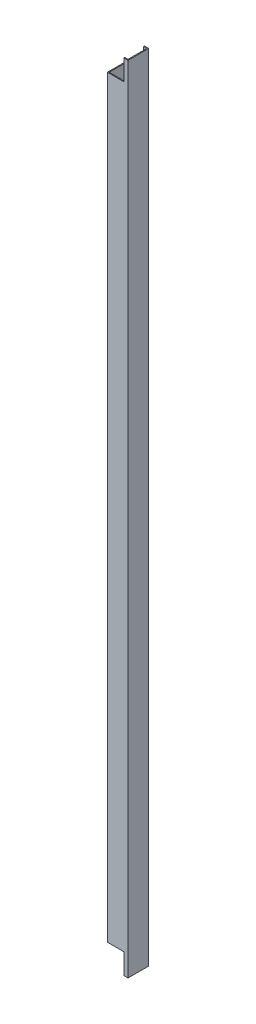
SolidWorks part; units mm, degrees
ref_plane "Front Plane" through (0, 0, 0) normal (0, 0, 1) x (1, 0, 0)
ref_plane "Top Plane" through (0, 0, 0) normal (0, 1, 0) x (1, 0, 0)
ref_plane "Right Plane" through (0, 0, 0) normal (1, 0, 0) x (0, 0, -1)
sketch "Sketch1" plane through (0, 0, 0) normal (0, 1, 0) x (1, 0, 0)
  line L0 (0, 0) -> (0, 50)
  line L1 (0, 50) -> (50, 50)
  line L2 (50, 50) -> (50, 0)
  line L3 (50, 0) -> (0, 0)
  line L4 (2.2, 47.8) -> (47.8, 47.8)
  line L5 (47.8, 47.8) -> (47.8, 2.2)
  line L6 (47.8, 2.2) -> (2.2, 2.2)
  line L7 (2.2, 2.2) -> (2.2, 47.8)
  dimension "D1" = 50
  dimension "D2" = 50
  dimension "D3" = 2.2
extrude "Boss-Extrude1" add sketch "Sketch1" along normal blind 1923
sketch "Sketch2" plane through (0, 0, 0) normal (0, 0, 1) x (1, 0, 0)
  line L0 (0, 0) -> (0, 50)
  line L1 (0, 1923) -> (0, 0) construction
  line L2 (0, 50) -> (40, 50)
  line L3 (40, 50) -> (40, 0)
  line L5 (40, 0) -> (0, 0)
  line L6 (0, 1923) -> (40, 1923)
  line L7 (0, 1923) -> (50, 1923) construction
  line L8 (40, 1923) -> (40, 1873)
  line L9 (40, 1873) -> (0, 1873)
  line L10 (0, 1873) -> (0, 1923)
  dimension "D1" = 50
  dimension "D2" = 40
  dimension "D3" = 50
  dimension "D4" = 40
extrude "Cut-Extrude2" cut sketch "Sketch2" against normal blind 50
equation "\"SquareTube_length\"=1923.0"
equation "\"D1@Boss-Extrude1\"=\"SquareTube_length\""
equation "\"SquareTube_inFront1_cutDepth50_R\"=0.5"
equation "\"D1@Sketch2\" = \"SquareTube_inFront12_cutDepth50_R\""
equation "\"SquareTube_inFront1_cutDepth50_L\"=0.5"
equation "\"D3@Sketch2\" = \"SquareTube_inFront12_cutDepth50_L\""
equation "\"CarBeamWidth\"=700.0"
equation "\"MetalSheet_3mm_length\"=5030.0"
equation "\"MetalSheet_3mm_width\"=1923.0"
equation "\"MetalSheet_3mm_FloorCut_L_length\"=1764.0"
equation "\"MetalSheet_3mm_FloorCut_L_disdance\"=1665.0"
equation "\"MetalSheet_3mm_FloorCut_R_length\"=1764.0"
equation "\"MetalSheet_3mm_FloorCut_R_disdance\"=1665.0"
equation "\"indoorHeight\"=1940.0"
equation "\"x\"=66.0"
equation "\"da\"=62.0"
equation "\"SquareTube_wheel_length\"= 750"
equation "\"channelSteel_length\"=5030.0"
equation "\"SquareTube_inFront2_cutDepth50_R\"=0.5"
equation "\"SquareTube_inFront2_cutDepth50_L\"=0.5"
equation "\"SquareTube_inFront3_cutDepth50_R\"=0.5"
equation "\"SquareTube_inFront3_cutDepth50_L\"=0.5"
equation "\"SquareTube_inFront4_cutDepth50_R\"=0.5"
equation "\"SquareTube_inFront4_cutDepth50_L\"=0.5"
equation "\"SquareTube_inFront5_cutDepth50_R\"=50"
equation "\"SquareTube_inFront5_cutDepth50_L\"=50"
equation "\"SquareTube_inFront6_cutDepth50_R\"=50"
equation "\"SquareTube_inFront6_cutDepth50_L\"=50"
equation "\"SquareTube_inFront7_cutDepth50_R\"=50"
equation "\"SquareTube_inFront7_cutDepth50_L\"=50"
equation "\"SquareTube_inFront8_cutDepth50_R\"=50"
equation "\"SquareTube_inFront8_cutDepth50_L\"=50"
equation "\"SquareTube_inFront9_cutDepth50_R\"=50"
equation "\"SquareTube_inFront9_cutDepth50_L\"=50"
equation "\"SquareTube_inFront10_cutDepth50_R\"=50"
equation "\"SquareTube_inFront10_cutDepth50_L\"=50"
equation "\"SquareTube_inBack1_cutDepth50_R\"=50"
equation "\"SquareTube_inBack1_cutDepth50_L\"=50"
equation "\"SquareTube_inBack2_cutDepth50_R\"=50"
equation "\"SquareTube_inBack2_cutDepth50_L\"=50"
equation "\"SquareTube_inBack3_cutDepth50_R\"=50"
equation "\"SquareTube_inBack3_cutDepth50_L\"=50"
equation "\"SquareTube_inBack4_cutDepth50_R\"=50"
equation "\"SquareTube_inBack4_cutDepth50_L\"=50"
equation "\"SquareTube_inBack5_cutDepth50_R\"=50"
equation "\"SquareTube_inBack5_cutDepth50_L\"=50"
equation "\"SquareTube_inBack6_cutDepth50_R\"=0.5"
equation "\"SquareTube_inBack6_cutDepth50_L\"=0.5"
equation "\"SquareTube_inFront11_cutDepth50_R\"=50"
equation "\"SquareTube_inFront11_cutDepth50_L\"=50"
equation "\"SquareTube_inFront12_cutDepth50_R\"=50"
equation "\"SquareTube_inFront12_cutDepth50_L\"=50"
equation "\"SquareTube_inFront13_cutDepth50_R\"=50"
equation "\"SquareTube_inFront13_cutDepth50_L\"=50"
equation "\"SquareTube_inFront14_cutDepth50_R\"=50"
equation "\"SquareTube_inFront14_cutDepth50_L\"=50"
equation "\"SquareTube_inBack7_cutDepth50_R\"=0.5"
equation "\"SquareTube_inBack7_cutDepth50_L\"=0.5"
equation "\"SquareTube_inBack8_cutDepth50_R\"=0.5"
equation "\"SquareTube_inBack8_cutDepth50_L\"=0.5"
